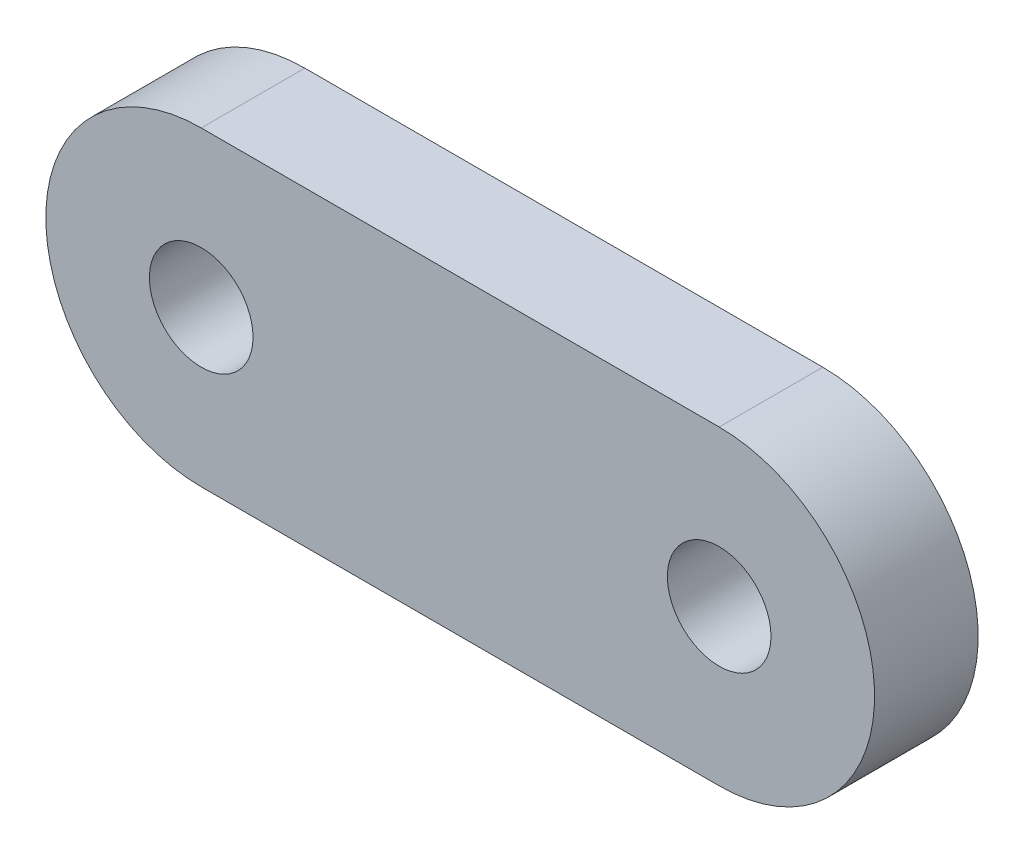
SolidWorks part; units mm, degrees
ref_plane "Front Plane" through (0, 0, 0) normal (0, 0, 1) x (1, 0, 0)
ref_plane "Top Plane" through (0, 0, 0) normal (0, 1, 0) x (1, 0, 0)
ref_plane "Right Plane" through (0, 0, 0) normal (1, 0, 0) x (0, 0, -1)
sketch "Sketch1" plane through (0, 0, 0) normal (0, 0, 1) x (1, 0, 0)
  line L0 (0, 0) -> (10, 0) construction
  line L1 (0, 3) -> (10, 3)
  line L2 (0, -3) -> (10, -3)
  arc A0 (0, 3) -> (0, -3) centre (0, 0) ccw
  arc A1 (10, -3) -> (10, 3) centre (10, 0) ccw
  circle A2 centre (10, 0) radius 1
  circle A3 centre (0, 0) radius 1
  point P3 (5, 0)
  dimension "D3" = 2
  dimension "D4" = 2
  dimension "D1" = 6
  dimension "D2" = 10
extrude "Boss-Extrude1" add sketch "Sketch1" along normal blind 2
